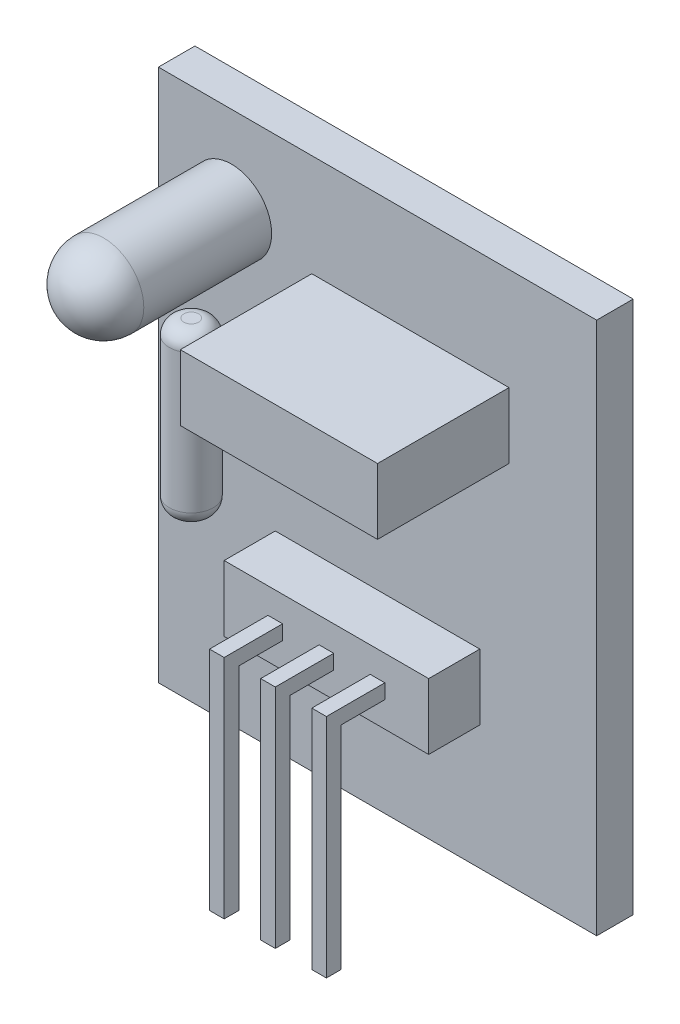
SolidWorks part; units mm, degrees
ref_plane "Front Plane" through (0, 0, 0) normal (0, 0, 1) x (1, 0, 0)
ref_plane "Top Plane" through (0, 0, 0) normal (0, 1, 0) x (1, 0, 0)
ref_plane "Right Plane" through (0, 0, 0) normal (1, 0, 0) x (0, 0, -1)
sketch "Sketch1" plane through (0, 0, 0) normal (0, 0, 1) x (1, 0, 0)
  line L1 (-7.62, 9.271) -> (7.62, 9.271)
  line L2 (-7.62, 9.271) -> (-7.62, -9.271)
  line L3 (-7.62, -9.271) -> (7.62, -9.271)
  line L4 (7.62, 9.271) -> (7.62, -9.271)
  line L5 (-7.62, 9.271) -> (7.62, -9.271) construction
  line L6 (-7.62, -9.271) -> (7.62, 9.271) construction
  point P0 (0, 0)
  dimension "D1" = 15.24
  dimension "D2" = 18.542
extrude "Boss-Extrude1" add sketch "Sketch1" along normal mid plane 1.27
sketch "Sketch2" plane through (0, 0, 0.635) normal (0, 0, 1) x (1, 0, 0)
  line L0 (-7.62, -9.271) -> (7.62, -9.271) construction
  line L1 (-3.556, -2.667) -> (3.556, -2.667)
  line L2 (-3.556, -2.667) -> (-3.556, -4.953)
  line L3 (-3.556, -4.953) -> (3.556, -4.953)
  line L4 (3.556, -2.667) -> (3.556, -4.953)
  line L5 (-3.556, -2.667) -> (3.556, -4.953) construction
  line L6 (-3.556, -4.953) -> (3.556, -2.667) construction
  point P0 (0, -3.81)
  dimension "D1" = 2.286
  dimension "D2" = 7.112
  dimension "D3" = 4.318
extrude "Boss-Extrude2" add sketch "Sketch2" along normal blind 1.778
sketch "Sketch3" plane through (0, 0, 2.413) normal (0, 0, 1) x (1, 0, 0)
  line L0 (-3.556, -2.667) -> (-3.556, -4.953) construction
  line L1 (-3.556, -3.81) -> (-1.778, -3.81) construction
  line L2 (-1.778, -3.81) -> (0, -3.81) construction
  line L3 (0, -3.81) -> (1.778, -3.81) construction
  line L4 (1.778, -3.81) -> (3.556, -3.81) construction
  line L5 (3.556, -4.953) -> (3.556, -2.667) construction
  line L7 (-2.032, -3.556) -> (-1.524, -3.556)
  line L8 (-2.032, -3.556) -> (-2.032, -4.064)
  line L9 (-2.032, -4.064) -> (-1.524, -4.064)
  line L10 (-1.524, -3.556) -> (-1.524, -4.064)
  line L11 (-2.032, -3.556) -> (-1.524, -4.064) construction
  line L12 (-2.032, -4.064) -> (-1.524, -3.556) construction
  line L13 (-0.254, -3.556) -> (0.254, -3.556)
  line L14 (-0.254, -3.556) -> (-0.254, -4.064)
  line L15 (-0.254, -4.064) -> (0.254, -4.064)
  line L16 (0.254, -3.556) -> (0.254, -4.064)
  line L17 (-0.254, -3.556) -> (0.254, -4.064) construction
  line L18 (-0.254, -4.064) -> (0.254, -3.556) construction
  line L19 (1.524, -3.556) -> (2.032, -3.556)
  line L20 (1.524, -3.556) -> (1.524, -4.064)
  line L21 (1.524, -4.064) -> (2.032, -4.064)
  line L22 (2.032, -3.556) -> (2.032, -4.064)
  line L23 (1.524, -3.556) -> (2.032, -4.064) construction
  line L24 (1.524, -4.064) -> (2.032, -3.556) construction
  dimension "D1" = 0.508
extrude "Boss-Extrude3" add sketch "Sketch3" along normal blind 2.032
sketch "Sketch4" plane through (0, -4.064, 0) normal (0, -1, 0) x (1, 0, 0)
  line L0 (-1.524, 4.445) -> (-1.524, 2.413) construction
  line L1 (-2.032, 4.445) -> (-1.524, 4.445)
  line L2 (-2.032, 4.445) -> (-2.032, 3.937)
  line L3 (-2.032, 3.937) -> (-1.524, 3.937)
  line L4 (-1.524, 4.445) -> (-1.524, 3.937)
  line L5 (-2.032, 4.445) -> (-1.524, 3.937) construction
  line L6 (-2.032, 3.937) -> (-1.524, 4.445) construction
  line L7 (-0.254, 4.445) -> (-0.254, 2.413) construction
  line L8 (-0.254, 3.937) -> (0.254, 3.937)
  line L9 (-0.254, 3.937) -> (-0.254, 4.445)
  line L10 (-0.254, 4.445) -> (0.254, 4.445)
  line L11 (0.254, 3.937) -> (0.254, 4.445)
  line L12 (-0.254, 3.937) -> (0.254, 4.445) construction
  line L13 (-0.254, 4.445) -> (0.254, 3.937) construction
  line L14 (2.032, 4.445) -> (2.032, 2.413) construction
  line L15 (1.524, 4.445) -> (2.032, 4.445)
  line L16 (1.524, 4.445) -> (1.524, 3.937)
  line L17 (1.524, 3.937) -> (2.032, 3.937)
  line L18 (2.032, 4.445) -> (2.032, 3.937)
  line L19 (1.524, 4.445) -> (2.032, 3.937) construction
  line L20 (1.524, 3.937) -> (2.032, 4.445) construction
  point P4 (-1.778, 4.191)
  point P12 (0, 4.191)
  point P20 (1.778, 4.191)
extrude "Boss-Extrude4" add sketch "Sketch4" along normal blind 7.366
sketch "Sketch8" plane through (0, 0, 0.635) normal (0, 0, 1) x (1, 0, 0)
  line L0 (7.62, -9.271) -> (7.62, 9.271) construction
  line L1 (-2.286, 5.715) -> (4.572, 5.715)
  line L2 (-2.286, 5.715) -> (-2.286, 3.429)
  line L3 (-2.286, 3.429) -> (4.572, 3.429)
  line L4 (4.572, 5.715) -> (4.572, 3.429)
  line L5 (-2.286, 5.715) -> (4.572, 3.429) construction
  line L6 (-2.286, 3.429) -> (4.572, 5.715) construction
  line L7 (7.62, 9.271) -> (-7.62, 9.271) construction
  point P0 (1.143, 4.572)
  dimension "D1" = 3.048
  dimension "D2" = 3.556
  dimension "D3" = 2.286
  dimension "D4" = 6.858
extrude "Boss-Extrude6" add sketch "Sketch8" along normal blind 4.572
sketch "Sketch9" plane through (0, 0, 0.635) normal (0, 0, 1) x (1, 0, 0)
  line L0 (-7.62, 9.271) -> (-7.62, -9.271) construction
  line L1 (7.62, 9.271) -> (-7.62, 9.271) construction
  circle A0 centre (-5.08, 6.223) radius 1.397
  dimension "D1" = 2.54
  dimension "D3" = 2.794
  dimension "D2" = 3.048
extrude "Boss-Extrude7" add sketch "Sketch9" along normal blind 5.842
fillet "Fillet1" radius 1.397 1 edges at (-3.683, 6.223, 6.477)
sketch "Sketch10" plane through (0, 0, 0) normal (0, 1, 0) x (1, 0, 0)
  line L0 (-7.62, -0.635) -> (-7.62, 0.635) construction
  line L3 (-6.477, -0.635) -> (-3.683, -0.635) construction
  circle A0 centre (-5.842, -1.27) radius 0.762
  point P4 (-5.842, -1.0874)
  dimension "D1" = 1.524
  dimension "D2" = 1.778
  dimension "D3" = 0.635
extrude "Boss-Extrude8" add sketch "Sketch10" along normal mid plane 5.842 separate body
fillet "Fillet2" radius 0.508 2 edges at (-5.842, -2.921, 2.032) (-5.842, 2.921, 2.032)
